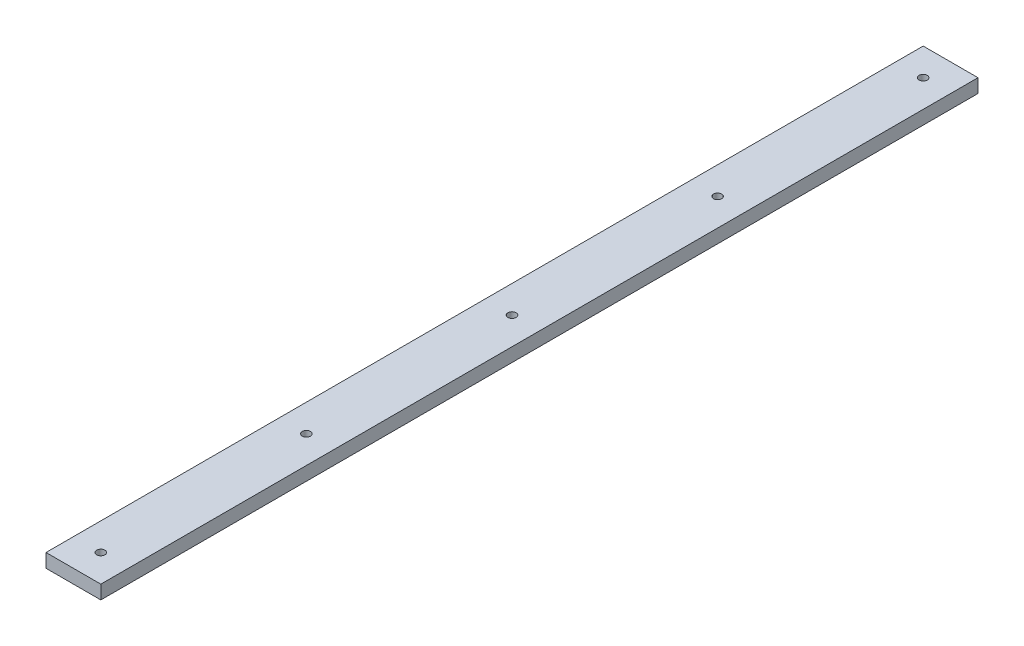
SolidWorks part; units mm, degrees
material "Настроенная пользователем пластмасса"
ref_plane "Спереди" through (0, 0, 0) normal (0, 0, 1) x (1, 0, 0)
ref_plane "Сверху" through (0, 0, 0) normal (0, 1, 0) x (1, 0, 0)
ref_plane "Справа" through (0, 0, 0) normal (1, 0, 0) x (0, 0, -1)
sketch "Эскиз1" plane through (0, 0, 0) normal (0, 1, 0) x (1, 0, 0)
  line L1 (-20, -320) -> (20, -320)
  line L2 (-20, -320) -> (-20, 320)
  line L3 (-20, 320) -> (20, 320)
  line L4 (20, -320) -> (20, 320)
  line L5 (0, 320) -> (0, -320) construction
  line L6 (-20, 0) -> (20, 0) construction
  point P0 (0, 0)
  dimension "D1" = 40
  dimension "D2" = 640
extrude "Бобышка-Вытянуть1" add sketch "Эскиз1" along normal mid plane 10
sketch "Эскиз2" plane through (0, 5, 0) normal (0, 1, 0) x (1, 0, 0)
  line L0 (-20, -320) -> (20, -320) construction
  circle A0 centre (0, -300) radius 3
  dimension "D1" = 6
  dimension "D2" = 20
extrude "Вырез-Вытянуть1" cut sketch "Эскиз2" against normal through all
pattern_linear "Линейный массив1" count 5 spacing 150 along (0, 0, -1) of "Вырез-Вытянуть1"
chamfer "Фаска1" [suppressed] distance 3 angle 45
